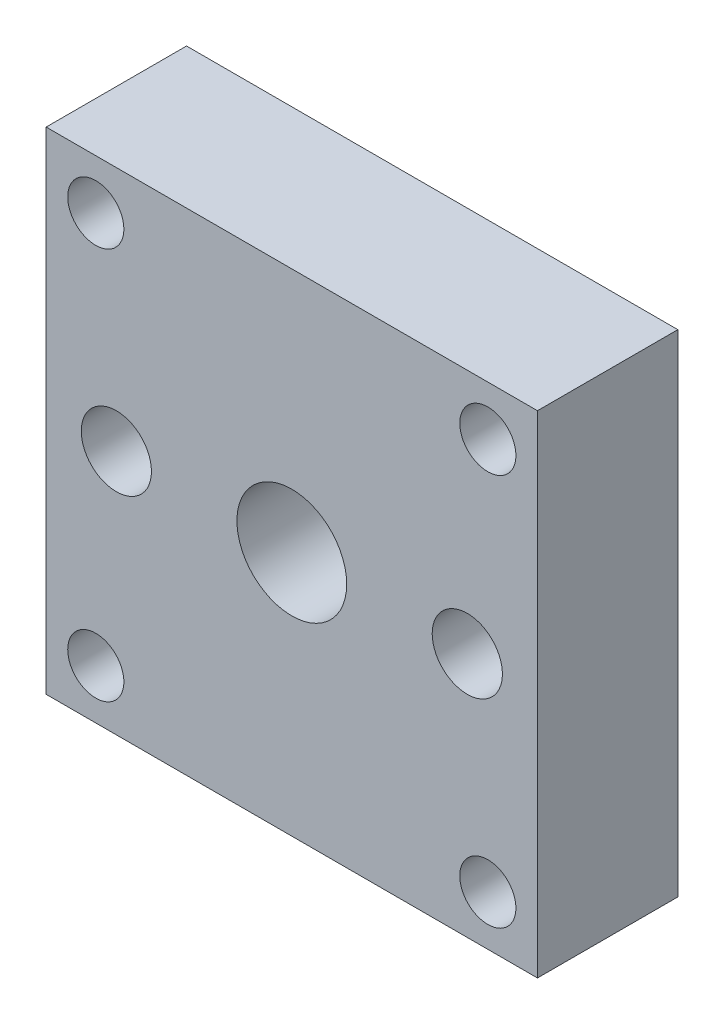
SolidWorks part; units mm, degrees
ref_plane "Front Plane" through (0, 0, 0) normal (0, 0, 1) x (1, 0, 0)
ref_plane "Top Plane" through (0, 0, 0) normal (0, 1, 0) x (1, 0, 0)
ref_plane "Right Plane" through (0, 0, 0) normal (1, 0, 0) x (0, 0, -1)
sketch "Sketch1" plane through (0, 0, 0) normal (0, 0, 1) x (1, 0, 0)
  line L0 (25.5319, -5.0588) -> (-9.4681, -5.0588) construction
  line L1 (-9.4681, 12.4412) -> (25.5319, 12.4412)
  line L2 (-9.4681, 12.4412) -> (-9.4681, -22.5588)
  line L3 (-9.4681, -22.5588) -> (25.5319, -22.5588)
  line L4 (25.5319, 12.4412) -> (25.5319, -22.5588)
  line L5 (-9.4681, 12.4412) -> (25.5319, -22.5588) construction
  line L6 (-9.4681, -22.5588) -> (25.5319, 12.4412) construction
  line L7 (8.0319, 12.4412) -> (8.0319, -22.5588) construction
  circle A0 centre (8.0319, -5.0588) radius 3.91
  circle A1 centre (21.9964, -19.0233) radius 2
  circle A2 centre (21.9964, 8.9057) radius 2
  circle A3 centre (-5.9325, -19.0233) radius 2
  circle A4 centre (-5.9325, 8.9057) radius 2
  circle A5 centre (-4.4681, -5.0588) radius 2.5
  circle A6 centre (20.5319, -5.0588) radius 2.5
  point P4 (8.0319, -5.0588)
  dimension "D3" = 7.82
  dimension "D4" = 4
  dimension "D6" = 5
  dimension "D1" = 35
  dimension "D2" = 35
  dimension "D5" = 5
extrude "Boss-Extrude1" add sketch "Sketch1" along normal blind 10
